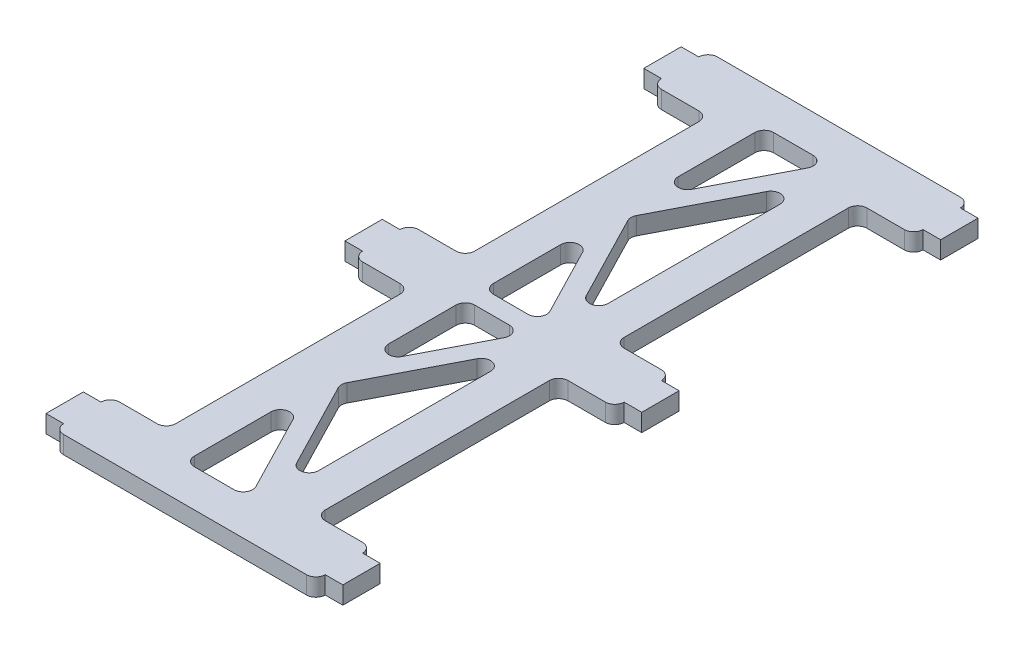
SolidWorks part; units mm, degrees
ref_plane "Front Plane" through (0, 0, 0) normal (0, 0, 1) x (1, 0, 0)
ref_plane "Top Plane" through (0, 0, 0) normal (0, 1, 0) x (1, 0, 0)
ref_plane "Right Plane" through (0, 0, 0) normal (1, 0, 0) x (0, 0, -1)
sketch "Sketch1" plane through (0, 34.29, 0) normal (0, 1, 0) x (1, 0, 0)
  line L0 (16.0528, 190.5) -> (19.05, 190.5) construction
  line L1 (0, -190.5) -> (0, 187.198) construction
  line L2 (38.1028, 187.198) -> (35.1028, 187.198) construction
  line L3 (35.1028, -190.5) -> (38.1, -190.5) construction
  line L5 (-12.7, 65.0875) -> (12.7, 65.0875)
  line L6 (-12.7, 65.0875) -> (-12.7, 176.2125)
  line L7 (-12.7, 176.2125) -> (12.7, 176.2125)
  line L8 (12.7, 65.0875) -> (12.7, 176.2125)
  line L9 (-12.7, 65.0875) -> (12.7, 176.2125) construction
  line L10 (-12.7, 176.2125) -> (12.7, 65.0875) construction
  point P0 (0, 120.65)
  dimension "D1" = 111.125
  dimension "D2" = 25.4
  dimension "D3" = 14.2875
extrude "Boss-Extrude1" add sketch "Sketch1" along normal mid plane 3 contours L7 L8 L5 L6
sketch "Sketch2" plane through (0, 35.79, 0) normal (0, 1, 0) x (1, 0, 0)
  line L0 (0, 176.2125) -> (0, 65.0186) construction
  line L1 (-12.7, 176.2125) -> (12.7, 176.2125) construction
  line L2 (12.7, 120.65) -> (-12.7, 120.65) construction
  line L5 (-22.225, 176.2125) -> (-12.7, 166.6875) construction
  line L6 (22.225, 166.6875) -> (12.7, 166.6875)
  line L7 (22.225, 166.6875) -> (22.225, 176.2125)
  line L8 (22.225, 176.2125) -> (12.7, 176.2125)
  line L9 (12.7, 166.6875) -> (12.7, 176.2125)
  line L10 (22.225, 166.6875) -> (12.7, 176.2125) construction
  line L11 (22.225, 176.2125) -> (12.7, 166.6875) construction
  line L12 (-22.225, 166.6875) -> (-12.7, 176.2125) construction
  line L13 (-12.7, 166.6875) -> (-12.7, 176.2125)
  line L14 (-22.225, 176.2125) -> (-12.7, 176.2125)
  line L15 (-22.225, 166.6875) -> (-22.225, 176.2125)
  line L16 (-22.225, 166.6875) -> (-12.7, 166.6875)
  line L17 (22.225, 115.8875) -> (12.7, 115.8875)
  line L18 (22.225, 115.8875) -> (22.225, 125.4125)
  line L19 (22.225, 125.4125) -> (12.7, 125.4125)
  line L20 (12.7, 115.8875) -> (12.7, 125.4125)
  line L21 (22.225, 115.8875) -> (12.7, 125.4125) construction
  line L22 (22.225, 125.4125) -> (12.7, 115.8875) construction
  line L23 (-12.7, 115.8875) -> (-12.7, 125.4125)
  line L24 (-22.225, 125.4125) -> (-12.7, 125.4125)
  line L25 (-22.225, 115.8875) -> (-22.225, 125.4125)
  line L26 (-22.225, 115.8875) -> (-12.7, 115.8875)
  line L27 (-22.225, 125.4125) -> (-12.7, 115.8875) construction
  line L28 (-22.225, 115.8875) -> (-12.7, 125.4125) construction
  line L29 (22.225, 65.0875) -> (12.7, 65.0875)
  line L30 (22.225, 65.0875) -> (22.225, 74.6125)
  line L31 (22.225, 74.6125) -> (12.7, 74.6125)
  line L32 (12.7, 65.0875) -> (12.7, 74.6125)
  line L33 (22.225, 65.0875) -> (12.7, 74.6125) construction
  line L34 (22.225, 74.6125) -> (12.7, 65.0875) construction
  line L35 (-12.7, 65.0875) -> (-12.7, 74.6125)
  line L36 (-22.225, 74.6125) -> (-12.7, 74.6125)
  line L37 (-22.225, 65.0875) -> (-22.225, 74.6125)
  line L38 (-22.225, 65.0875) -> (-12.7, 65.0875)
  line L39 (-22.225, 74.6125) -> (-12.7, 65.0875) construction
  line L40 (-22.225, 65.0875) -> (-12.7, 74.6125) construction
  point P7 (0, 0)
  point P11 (17.4625, 171.45)
  point P21 (-17.4625, 171.45)
  point P22 (0, 0)
  point P24 (17.4625, 120.65)
  point P33 (-17.4625, 120.65)
  point P34 (17.4625, 69.85)
  point P43 (-17.4625, 69.85)
  dimension "D1" = 9.525
  dimension "D2" = 9.525
  dimension "D4" = 50.8
  dimension "D3" = 3
extrude "Boss-Extrude2" add sketch "Sketch2" against normal up to surface (3 mm away) up to face at (0, 32.79, -120.65)
sketch "Sketch4" plane through (0, 35.79, 0) normal (0, 1, 0) x (1, 0, 0)
  line L0 (12.7, 125.4125) -> (12.7, 166.6875) construction
  line L1 (-6.35, 169.8625) -> (6.35, 169.8625)
  line L2 (-6.35, 169.8625) -> (-6.35, 71.4375)
  line L3 (-6.35, 71.4375) -> (6.35, 71.4375)
  line L4 (6.35, 169.8625) -> (6.35, 71.4375)
  line L5 (-6.35, 169.8625) -> (6.35, 71.4375) construction
  line L6 (-6.35, 71.4375) -> (6.35, 169.8625) construction
  line L7 (-12.7, 125.4125) -> (-12.7, 166.6875) construction
  line L8 (-22.225, 176.2125) -> (22.225, 176.2125) construction
  line L9 (-22.225, 65.0875) -> (22.225, 65.0875) construction
  line L10 (-6.35, 96.0438) -> (6.35, 96.0438) construction
  line L12 (-6.35, 96.0438) -> (6.35, 120.65) construction
  line L13 (6.35, 120.65) -> (-6.35, 145.2563) construction
  line L14 (6.35, 71.4375) -> (-6.35, 96.0438) construction
  line L15 (-6.35, 145.2563) -> (6.35, 145.2563) construction
  line L17 (7.7607, 72.1656) -> (-4.6953, 96.299)
  line L18 (-6.35, 145.2563) -> (6.35, 169.8625) construction
  line L19 (6.35, 120.65) -> (-6.35, 120.65) construction
  line L20 (-7.7607, 96.7718) -> (4.9393, 121.3781)
  line L21 (4.9393, 70.7094) -> (-8.0047, 95.7885)
  line L22 (6.35, 119.0625) -> (-6.35, 119.0625)
  line L23 (4.9393, 119.9219) -> (-8.1365, 145.2563)
  line L24 (-8.1365, 145.2563) -> (4.9393, 170.5906)
  line L25 (-4.6953, 96.299) -> (7.9145, 169.5933) construction
  line L26 (-4.9393, 95.3157) -> (7.7607, 119.9219)
  line L27 (-6.35, 96.0438) -> (6.35, 169.8625) construction
  line L29 (6.35, 122.2375) -> (-6.35, 122.2375)
  line L30 (-8.0047, 95.7885) -> (4.7855, 170.1317) construction
  line L31 (7.7607, 121.3781) -> (-4.5635, 145.2563)
  line L32 (-4.5635, 145.2563) -> (7.7607, 169.1344)
  point P0 (0, 120.65)
  dimension "D1" = 6.35
  dimension "D2" = 6.35
  dimension "D3" = 6.35
  dimension "D4" = 6.35
  dimension "D7" = 1.5875
  dimension "D8" = 1.5875
  dimension "D9" = 1.5875
  dimension "D10" = 1.5875
extrude "Cut-Extrude1" cut sketch "Sketch4" against normal through all contours L3 L21 L2 | L26 L17 L4 | L20 L22 L2 | L29 L23 L2 | L32 L31 L4 | L2 L24 L1
fillet "Fillet1" radius 1.5875 38 edges at (-6.35, 34.29, -92.5825) (6.35, 34.29, -74.8988) (22.225, 34.29, -65.0875) (22.225, 34.29, -74.6125) (12.7, 34.29, -74.6125) (12.7, 34.29, -115.8875) (22.225, 34.29, -115.8875) (22.225, 34.29, -125.4125) (12.7, 34.29, -125.4125) (12.7, 34.29, -166.6875) (22.225, 34.29, -166.6875) (22.225, 34.29, -176.2125) (-22.225, 34.29, -166.6875) (-12.7, 34.29, -166.6875) (-12.7, 34.29, -125.4125) (-22.225, 34.29, -125.4125) (-22.225, 34.29, -115.8875) (-12.7, 34.29, -115.8875) (-12.7, 34.29, -74.6125) (-22.225, 34.29, -74.6125) (-22.225, 34.29, -65.0875) (4.5635, 34.29, -71.4375) (-22.225, 34.29, -176.2125) (-6.35, 34.29, -141.795) (3.7442, 34.29, -122.2375) (-6.35, 34.29, -122.2375) (6.35, 34.29, -117.1887) (6.35, 34.29, -124.1113) (-4.5635, 34.29, -145.2563) (6.35, 34.29, -166.4012) (-6.35, 34.29, -169.8625) (4.5635, 34.29, -169.8625) (-6.35, 34.29, -148.7175) (-6.35, 34.29, -99.505) (-6.35, 34.29, -119.0625) (3.7442, 34.29, -119.0625) (-6.35, 34.29, -71.4375) (-4.5635, 34.29, -96.0438)
sketch "Sketch5" plane through (0, 35.79, 0) normal (0, 1, 0) x (1, 0, 0)
  line L0 (22.225, 168.275) -> (22.225, 174.625) construction
  line L1 (25.225, 168.275) -> (22.225, 168.275)
  line L2 (25.225, 168.275) -> (25.225, 174.625)
  line L3 (25.225, 174.625) -> (22.225, 174.625)
  line L4 (22.225, 168.275) -> (22.225, 174.625)
  line L5 (25.225, 168.275) -> (22.225, 174.625) construction
  line L6 (25.225, 174.625) -> (22.225, 168.275) construction
  line L7 (22.225, 168.275) -> (22.225, 174.625) construction
  line L8 (22.225, 171.45) -> (23.725, 171.45) construction
  line L9 (0, 196.0278) -> (0, 0) construction
  line L10 (-22.225, 171.45) -> (-23.725, 171.45) construction
  line L11 (-25.225, 174.625) -> (-22.225, 168.275) construction
  line L12 (-25.225, 168.275) -> (-22.225, 174.625) construction
  line L13 (-22.225, 168.275) -> (-22.225, 174.625)
  line L14 (-25.225, 174.625) -> (-22.225, 174.625)
  line L15 (-25.225, 168.275) -> (-25.225, 174.625)
  line L16 (-25.225, 168.275) -> (-22.225, 168.275)
  line L17 (25.225, 117.475) -> (22.225, 117.475)
  line L18 (25.225, 117.475) -> (25.225, 123.825)
  line L19 (25.225, 123.825) -> (22.225, 123.825)
  line L20 (22.225, 117.475) -> (22.225, 123.825)
  line L21 (25.225, 117.475) -> (22.225, 123.825) construction
  line L22 (25.225, 123.825) -> (22.225, 117.475) construction
  line L23 (22.225, 120.65) -> (23.725, 120.65) construction
  line L24 (-22.225, 117.475) -> (-22.225, 123.825)
  line L25 (-25.225, 123.825) -> (-22.225, 123.825)
  line L26 (-25.225, 117.475) -> (-25.225, 123.825)
  line L27 (-25.225, 117.475) -> (-22.225, 117.475)
  line L28 (-22.225, 120.65) -> (-23.725, 120.65) construction
  line L29 (-25.225, 123.825) -> (-22.225, 117.475) construction
  line L30 (-25.225, 117.475) -> (-22.225, 123.825) construction
  line L31 (25.225, 66.675) -> (22.225, 66.675)
  line L32 (25.225, 66.675) -> (25.225, 73.025)
  line L33 (25.225, 73.025) -> (22.225, 73.025)
  line L34 (22.225, 66.675) -> (22.225, 73.025)
  line L35 (25.225, 66.675) -> (22.225, 73.025) construction
  line L36 (25.225, 73.025) -> (22.225, 66.675) construction
  line L37 (22.225, 69.85) -> (23.725, 69.85) construction
  line L38 (-22.225, 66.675) -> (-22.225, 73.025)
  line L39 (-25.225, 73.025) -> (-22.225, 73.025)
  line L40 (-25.225, 66.675) -> (-25.225, 73.025)
  line L41 (-25.225, 66.675) -> (-22.225, 66.675)
  line L42 (-22.225, 69.85) -> (-23.725, 69.85) construction
  line L43 (-25.225, 73.025) -> (-22.225, 66.675) construction
  line L44 (-25.225, 66.675) -> (-22.225, 73.025) construction
  line L45 (-23.725, 171.45) -> (-23.725, 120.65) construction
  point P0 (23.725, 171.45)
  point P7 (23.725, 120.65)
  point P21 (-23.725, 171.45)
  point P35 (-23.725, 120.65)
  point P36 (23.725, 69.85)
  point P49 (-23.725, 69.85)
  dimension "D1" = 3
  dimension "D2" = 6.35
  dimension "D4" = 50.8
  dimension "D3" = 3
extrude "Boss-Extrude3" add sketch "Sketch5" against normal up to surface (3 mm away)
